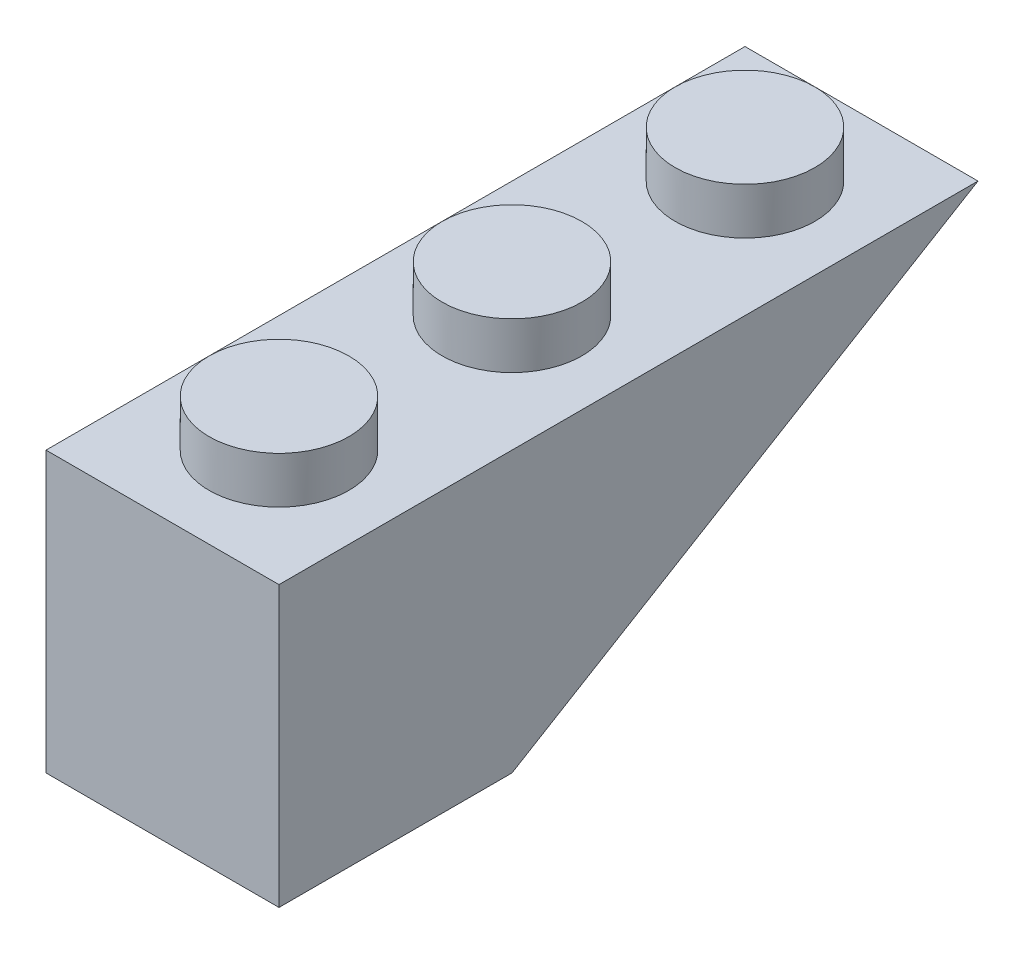
SolidWorks part; units mm, degrees
ref_plane "Front Plane" through (0, 0, 0) normal (0, 0, 1) x (1, 0, 0)
ref_plane "Top Plane" through (0, 0, 0) normal (0, 1, 0) x (1, 0, 0)
ref_plane "Right Plane" through (0, 0, 0) normal (1, 0, 0) x (0, 0, -1)
sketch "Sketch1" plane through (0, 0, 0) normal (1, 0, 0) x (0, 0, -1)
  line L0 (0, 0) -> (8, 0)
  line L3 (0, 9.6) -> (0, 0)
  line L4 (0, 9.6) -> (8, 9.6)
  line L5 (8, 9.6) -> (8, 0)
  dimension "D1" = 8
  dimension "D3" = 9.6
extrude "Boss-Extrude1" add sketch "Sketch1" along normal blind 8
shell "Shell2" thickness 1.6
sketch "Sketch3" plane through (0, 0, 0) normal (1, 0, 0) x (0, 0, -1)
  line L0 (8, 0) -> (24, 9.6)
  line L1 (24, 9.6) -> (8, 9.6)
  line L2 (8, 0) -> (8, 9.6)
  dimension "D1" = 16
extrude "Boss-Extrude3" add sketch "Sketch3" along normal blind 8
sketch "Sketch4" plane through (0, 9.6, 0) normal (0, 1, 0) x (1, 0, 0)
  line L0 (4, 0) -> (4, 4) construction
  line L1 (8, 0) -> (0, 0) construction
  circle A0 centre (4, 4) radius 2.4
  dimension "D2" = 4.8
  dimension "D1" = 4
extrude "Boss-Extrude4" add sketch "Sketch4" along normal blind 1.6
pattern_linear "LPattern2" count 3 spacing 8 along (0, 0, -1) of "Boss-Extrude4"
